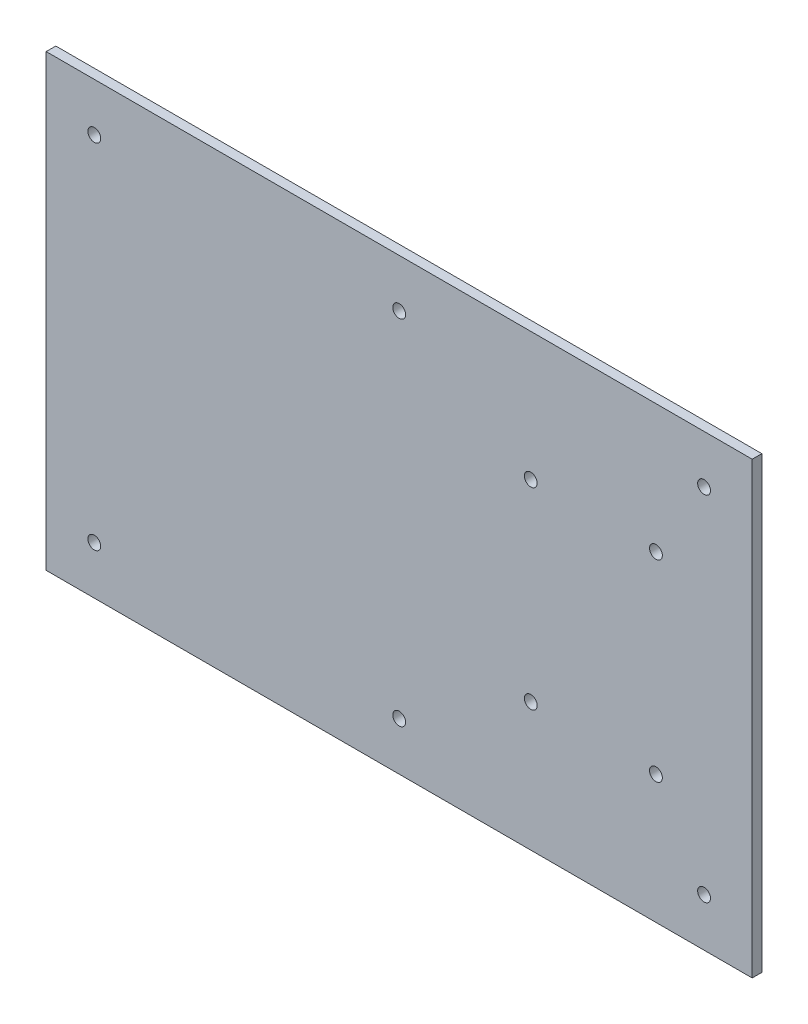
SolidWorks part; units mm, degrees
material "ABS"
ref_plane "Ön Düzlem" through (0, 0, 0) normal (0, 0, 1) x (1, 0, 0)
ref_plane "Üst Düzlem" through (0, 0, 0) normal (0, 1, 0) x (1, 0, 0)
ref_plane "Sağ Düzlem" through (0, 0, 0) normal (1, 0, 0) x (0, 0, -1)
sketch "Çizim1" plane through (0, 0, 0) normal (0, 0, 1) x (1, 0, 0)
  line L1 (0, 0) -> (220, 0)
  line L2 (0, 0) -> (0, 140)
  line L3 (0, 140) -> (220, 140)
  line L4 (220, 0) -> (220, 140)
  dimension "D1" = 220
  dimension "D2" = 140
extrude "Yükseklik-Ekstrüzyon1" add sketch "Çizim1" along normal blind 3
sketch "Çizim2" plane through (0, 0, 3) normal (0, 0, 1) x (1, 0, 0)
  line L0 (220, 140) -> (0, 140) construction
  line L1 (0, 140) -> (0, 0) construction
  line L2 (220, 0) -> (220, 140) construction
  line L3 (0, 70) -> (220, 70) construction
  circle A0 centre (15, 125) radius 2
  circle A1 centre (205, 125) radius 2
  circle A2 centre (110, 125) radius 2
  circle A3 centre (205, 15) radius 2
  circle A4 centre (110, 15) radius 2
  circle A5 centre (15, 15) radius 2
  dimension "D1" = 4
  dimension "D2" = 15
  dimension "D4" = 4
  dimension "D7" = 4
  dimension "D3" = 15
  dimension "D5" = 15
  dimension "D6" = 15
  dimension "D8" = 15
  dimension "D9" = 95
extrude "Kes-Ekstrüzyon1" cut sketch "Çizim2" against normal blind 3
sketch "Çizim4" plane through (0, 0, 3) normal (0, 0, 1) x (1, 0, 0)
  line L0 (0, 0) -> (220, 0) construction
  line L1 (220, 0) -> (220, 140) construction
  line L2 (220, 70) -> (0, 70) construction
  line L3 (0, 140) -> (0, 0) construction
  circle A0 centre (190, 40) radius 2
  circle A1 centre (151, 40) radius 2
  circle A2 centre (190, 100) radius 2
  circle A3 centre (151, 100) radius 2
  dimension "D1" = 4
  dimension "D3" = 4
  dimension "D2" = 40
  dimension "D4" = 40
  dimension "D5" = 39
  dimension "D6" = 30
extrude "Kes-Ekstrüzyon3" cut sketch "Çizim4" against normal blind 10
